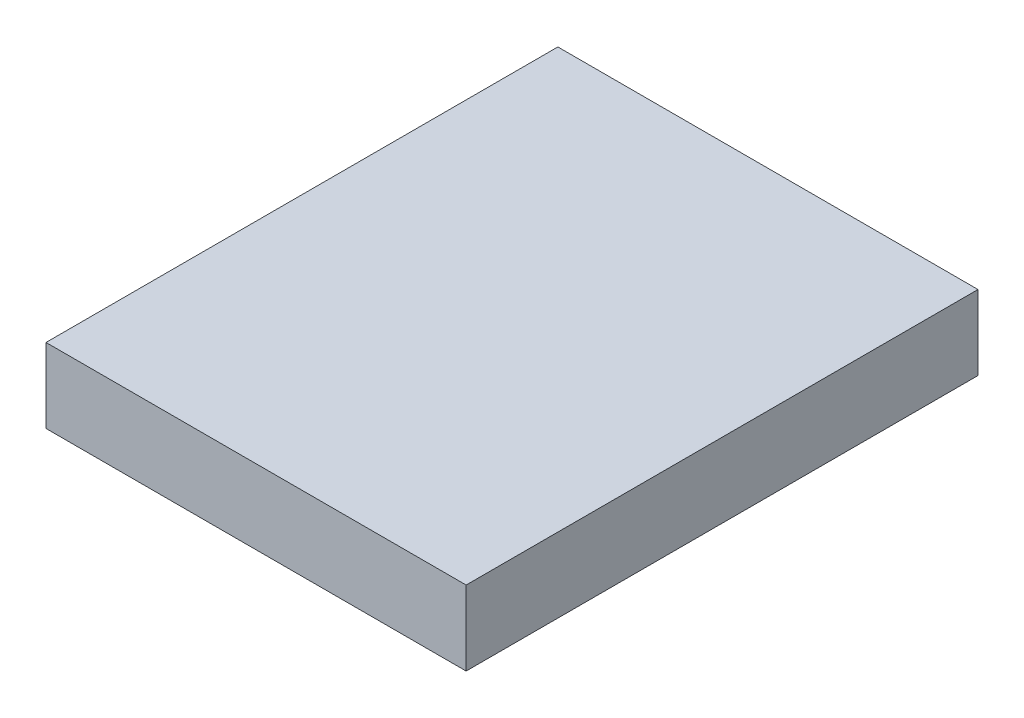
SolidWorks part; units mm, degrees
ref_plane "Plan de face" through (0, 0, 0) normal (0, 0, 1) x (1, 0, 0)
ref_plane "Plan de dessus" through (0, 0, 0) normal (0, 1, 0) x (1, 0, 0)
ref_plane "Plan de droite" through (0, 0, 0) normal (1, 0, 0) x (0, 0, -1)
sketch "Esquisse1" plane through (0, 0, 0) normal (0, 0, 1) x (1, 0, 0)
  line L1 (0, 0) -> (366.46, 0)
  line L2 (0, 0) -> (0, 65)
  line L3 (0, 65) -> (366.46, 65)
  line L4 (366.46, 0) -> (366.46, 65)
  dimension "D3" = 366.46
  dimension "D1" = 65
extrude "Boss.-Extru.2" add sketch "Esquisse1" along normal blind 446.46
equation "\"L\"=366.46"
equation "\"H\"= 65"
equation "\"W\"= 446.46"
equation "\"R\"= 100"
equation "\"D1@Boss.-Extru.2\"=\"W\""
equation "\"D3@Esquisse1\"=\"L\""
